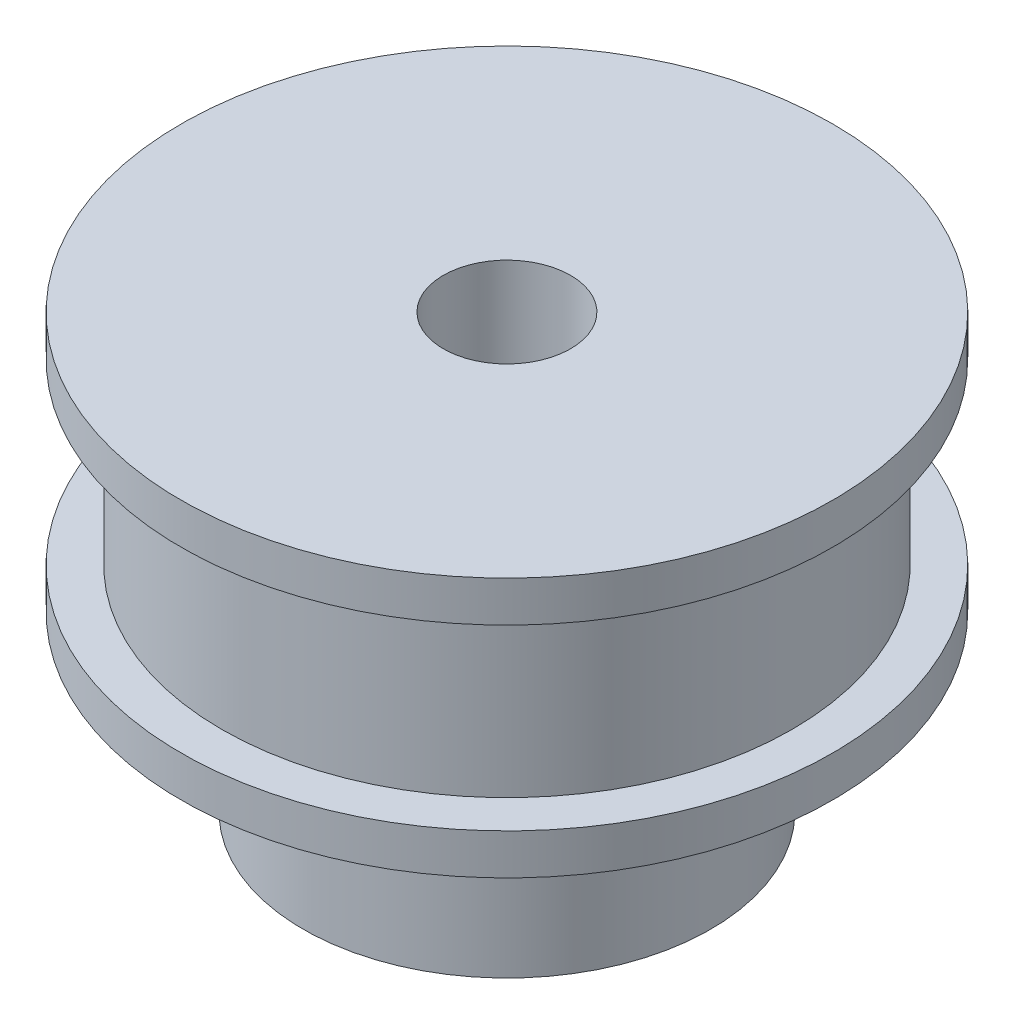
SolidWorks part; units mm, degrees
ref_plane "Front Plane" through (0, 0, 0) normal (0, 0, 1) x (1, 0, 0)
ref_plane "Top Plane" through (0, 0, 0) normal (0, 1, 0) x (1, 0, 0)
ref_plane "Right Plane" through (0, 0, 0) normal (1, 0, 0) x (0, 0, -1)
sketch "Sketch1" plane through (0, 0, 0) normal (0, 0, 1) x (1, 0, 0)
  line L0 (8, 0) -> (8, 6.8)
  line L1 (8, 6.8) -> (12.8, 6.8)
  line L2 (12.8, 6.8) -> (12.8, 8.4)
  line L3 (12.8, 8.4) -> (11.2, 8.4)
  line L4 (11.2, 8.4) -> (11.2, 15.4)
  line L5 (12.8, 17) -> (2.5, 17)
  line L6 (0, 0) -> (0, 17) construction
  line L7 (8, 0) -> (2.5, 0)
  line L8 (2.5, 17) -> (2.5, 0)
  line L9 (11.2, 15.4) -> (12.8, 15.4)
  line L10 (12.8, 15.4) -> (12.8, 17)
  dimension "D1" = 17
  dimension "D2" = 7
  dimension "D3" = 11.2
  dimension "D4" = 2.5
  dimension "D5" = 8
  dimension "D6" = 1.6
  dimension "D7" = 12.8
revolve "Revolve1" add sketch "Sketch1" angle 360 about L6
